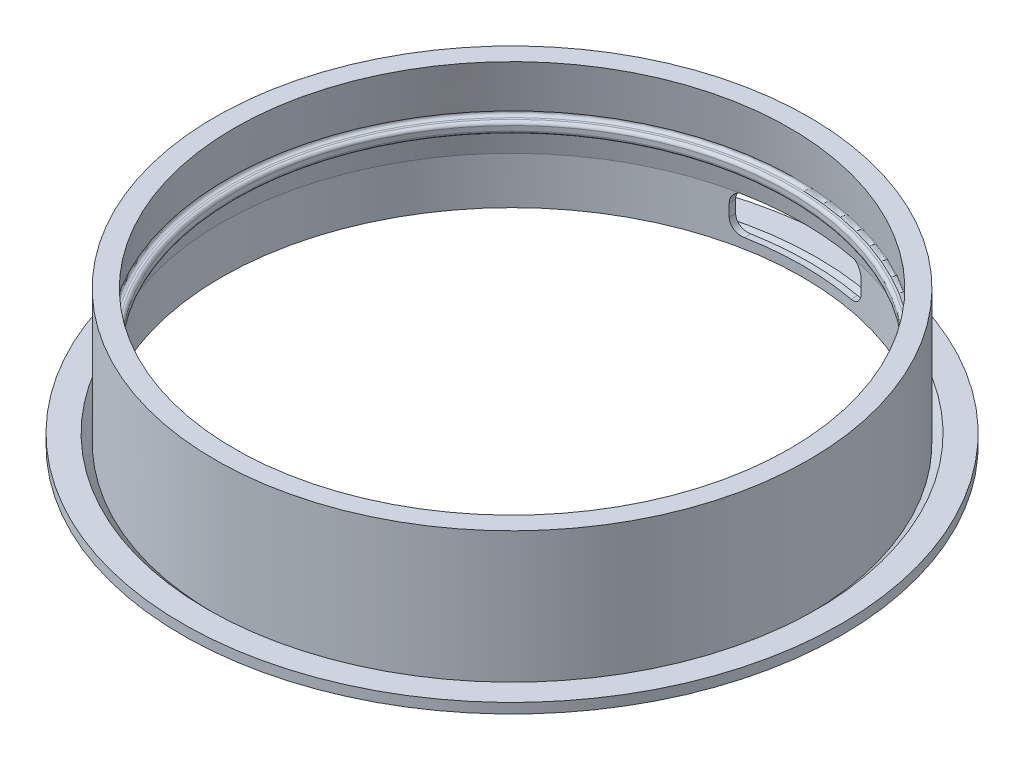
SolidWorks part; units mm, degrees
ref_plane "Front Plane" through (0, 0, 0) normal (0, 0, 1) x (1, 0, 0)
ref_plane "Top Plane" through (0, 0, 0) normal (0, 1, 0) x (1, 0, 0)
ref_plane "Right Plane" through (0, 0, 0) normal (1, 0, 0) x (0, 0, -1)
sketch "Sketch2" plane through (0, 0, 0) normal (0, 0, 1) x (1, 0, 0)
  line L0 (46.3, 0) -> (46.3, 21.6)
  line L1 (46.3, 21.6) -> (47.3, 21.6)
  line L2 (47.3, 21.6) -> (47.3, 1.6)
  line L3 (47.3, 1.6) -> (52.5, 1.6)
  line L4 (52.5, 1.6) -> (52.5, 0)
  line L5 (52.5, 0) -> (46.3, 0)
  line L6 (0, -1000) -> (0, 49000) construction
  dimension "D1" = 52.5
  dimension "D2" = 46.3
  dimension "D3" = 20
  dimension "D4" = 1.6
  dimension "D5" = 1
revolve "Revolve1" add sketch "Sketch2" angle 360 about L6
sketch "Sketch4" plane through (0, 0, 0) normal (0, 0, 1) x (1, 0, 0)
  line L1 (-10.5, 7.6) -> (10.5, 7.6)
  line L2 (-10.5, 7.6) -> (-10.5, 1.6)
  line L3 (-10.5, 1.6) -> (10.5, 1.6)
  line L4 (10.5, 7.6) -> (10.5, 1.6)
  line L5 (-10.5, 7.6) -> (10.5, 1.6) construction
  line L6 (-10.5, 1.6) -> (10.5, 7.6) construction
  line L7 (52.5, 1.6) -> (-52.5, 1.6) construction
  point P0 (0, 4.6)
  dimension "D1" = 21
  dimension "D2" = 6
extrude "Cut-Extrude1" cut sketch "Sketch4" against normal up to next
fillet "Fillet1" radius 2 4 edges at (10.5, 1.6, -45.6068) (10.5, 7.6, -45.6068) (-10.5, 7.6, -45.6068) (-10.5, 1.6, -45.6068)
sketch "Sketch6" plane through (0, 0, 0) normal (0, 0, 1) x (1, 0, 0)
  line L0 (-46.3, 21.6) -> (-46.3, 7.5)
  line L1 (-46.3, 7.5) -> (-44.243, 21.6)
  line L2 (-44.243, 21.6) -> (-46.3, 21.6)
  line L3 (-46.3, 0) -> (46.3, 0) construction
  line L4 (-45.6873, 11.7) -> (-44, 11.7)
  line L5 (-44, 11.7) -> (-44, 13.45)
  line L6 (-44, 13.45) -> (-45.432, 13.45)
  line L7 (0, -1000) -> (0, 49000) construction
  dimension "D1" = 7.5
  dimension "D2" = 8.3
  dimension "D3" = 4.2
  dimension "D4" = 1.75
  dimension "D5" = 44
revolve "Revolve2" add sketch "Sketch6" angle 360 about L7
fillet "Fillet2" radius 0.5 4 edges at (45.6873, 11.7, 0) (44, 11.7, 0) (45.432, 13.45, 0) (44, 13.45, 0)
sketch "Sketch7" plane through (0, 0, 0) normal (0, 0, 1) x (1, 0, 0)
  line L0 (-47.3, 1.6) -> (-47.3, 0.35)
  line L1 (52.5, 1.6) -> (-52.5, 1.6) construction
  line L2 (-47.3, 0.35) -> (-48.55, 1.6)
  line L3 (-48.55, 1.6) -> (-47.3, 1.6)
  line L4 (-47.3, 21.6) -> (-47.3, 1.6) construction
  line L5 (0, 0) -> (0, 50000) construction
  dimension "D1" = 45
  dimension "D2" = 1.25
revolve "Cut-Revolve1" cut sketch "Sketch7" angle 360 about L5
